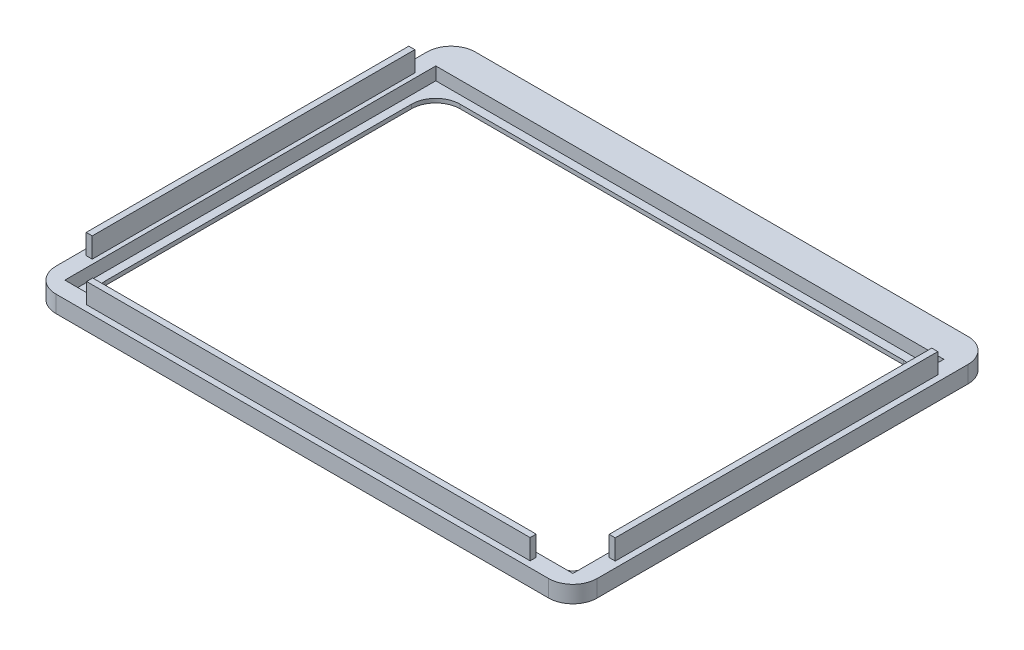
SolidWorks part; units mm, degrees
ref_plane "Front Plane" through (0, 0, 0) normal (0, 0, 1) x (1, 0, 0)
ref_plane "Top Plane" through (0, 0, 0) normal (0, 1, 0) x (1, 0, 0)
ref_plane "Right Plane" through (0, 0, 0) normal (1, 0, 0) x (0, 0, -1)
sketch "Sketch1" plane through (0, 0, 0) normal (0, 1, 0) x (1, 0, 0)
  line L1 (3, 0) -> (64.1, 0)
  line L2 (0, 3) -> (0, 49)
  line L3 (3, 52) -> (64.1, 52)
  line L4 (67.1, 3) -> (67.1, 49)
  arc A0 (0, 49) -> (3, 52) centre (3, 49) cw
  arc A1 (3, 0) -> (0, 3) centre (3, 3) cw
  arc A2 (64.1, 0) -> (67.1, 3) centre (64.1, 3) ccw
  arc A3 (64.1, 52) -> (67.1, 49) centre (64.1, 49) cw
  point P9 (0, 0)
  point P12 (67.1, 0)
  point P15 (67.1, 52)
  dimension "D3" = 3
  dimension "D1" = 67.1
  dimension "D2" = 52
extrude "Boss-Extrude1" add sketch "Sketch1" along normal blind 2.1
sketch "Sketch3" plane through (0, 2.1, 0) normal (0, 1, 0) x (1, 0, 0)
  line L0 (3, 0) -> (64.1, 0) construction
  line L1 (0, 49) -> (0, 3) construction
  line L2 (2.05, 2.05) -> (65.05, 2.05)
  line L3 (2.05, 2.05) -> (2.05, 48.05)
  line L4 (2.05, 48.05) -> (65.05, 48.05)
  line L5 (65.05, 2.05) -> (65.05, 48.05)
  dimension "D1" = 63
  dimension "D2" = 46
  dimension "D3" = 2.05
  dimension "D4" = 2.05
extrude "Cut-Extrude1" cut sketch "Sketch3" against normal blind 1.6
sketch "Sketch5" plane through (0, 0.5, 0) normal (0, 1, 0) x (1, 0, 0)
  line L0 (6.05, 47.05) -> (61.05, 47.05)
  line L1 (5.05, 48.05) -> (62.05, 48.05)
  line L2 (2.05, 45.05) -> (2.05, 5.05)
  line L3 (5.05, 2.05) -> (62.05, 2.05)
  line L4 (65.05, 45.05) -> (65.05, 5.05)
  line L5 (3.05, 44.05) -> (3.05, 6.05)
  line L6 (6.05, 3.05) -> (61.05, 3.05)
  line L7 (64.05, 44.05) -> (64.05, 6.05)
  arc A0 (2.05, 5.05) -> (5.05, 2.05) centre (5.05, 5.05) ccw
  arc A1 (62.05, 2.05) -> (65.05, 5.05) centre (62.05, 5.05) ccw
  arc A2 (62.05, 48.05) -> (65.05, 45.05) centre (62.05, 45.05) cw
  arc A3 (5.05, 48.05) -> (2.05, 45.05) centre (5.05, 45.05) ccw
  arc A4 (3.05, 6.05) -> (6.05, 3.05) centre (6.05, 6.05) ccw
  arc A5 (61.05, 3.05) -> (64.05, 6.05) centre (61.05, 6.05) ccw
  arc A6 (61.05, 47.05) -> (64.05, 44.05) centre (61.05, 44.05) cw
  arc A7 (6.05, 47.05) -> (3.05, 44.05) centre (6.05, 44.05) ccw
  point P10 (65.05, 2.05)
  point P15 (2.05, 48.05)
  dimension "D1" = 3
  dimension "D2" = 61
  dimension "D3" = 44
  dimension "D4" = 1
  dimension "D5" = 1
extrude "Cut-Extrude2" cut sketch "Sketch5" against normal blind 0.5 contours L0 A6 L7 A5 L6 A4 L5 A7
sketch "Sketch6" plane through (0, 2.1, 0) normal (0, 1, 0) x (1, 0, 0)
  line L0 (0, 26) -> (67.1, 26) construction
  line L1 (0, 49) -> (0, 3) construction
  line L2 (67.1, 3) -> (67.1, 49) construction
  line L3 (65.6, 46) -> (66.35, 46)
  line L4 (0.75, 46) -> (1.5, 46)
  line L5 (0.75, 46) -> (0.75, 6)
  line L6 (0.75, 6) -> (1.5, 6)
  line L7 (1.5, 46) -> (1.5, 6)
  line L8 (65.6, 46) -> (65.6, 6)
  line L9 (65.6, 6) -> (66.35, 6)
  line L10 (66.35, 46) -> (66.35, 6)
  line L11 (33.55, 0) -> (33.55, 52) construction
  line L12 (3, 0) -> (64.1, 0) construction
  line L13 (64.1, 52) -> (3, 52) construction
  line L15 (6.05, 1.5) -> (61.05, 1.5)
  line L16 (6.05, 1.5) -> (6.05, 0.75)
  line L17 (6.05, 0.75) -> (61.05, 0.75)
  line L18 (61.05, 1.5) -> (61.05, 0.75)
  point P10 (0.75, 26)
  point P15 (66.35, 26)
  point P26 (33.55, 0.75)
  dimension "D1" = 0.75
  dimension "D2" = 40
  dimension "D3" = 0.75
  dimension "D4" = 0.75
  dimension "D5" = 55
  dimension "D6" = 0.75
  dimension "D7" = 0.75
extrude "Boss-Extrude2" add sketch "Sketch6" along normal blind 2.5
